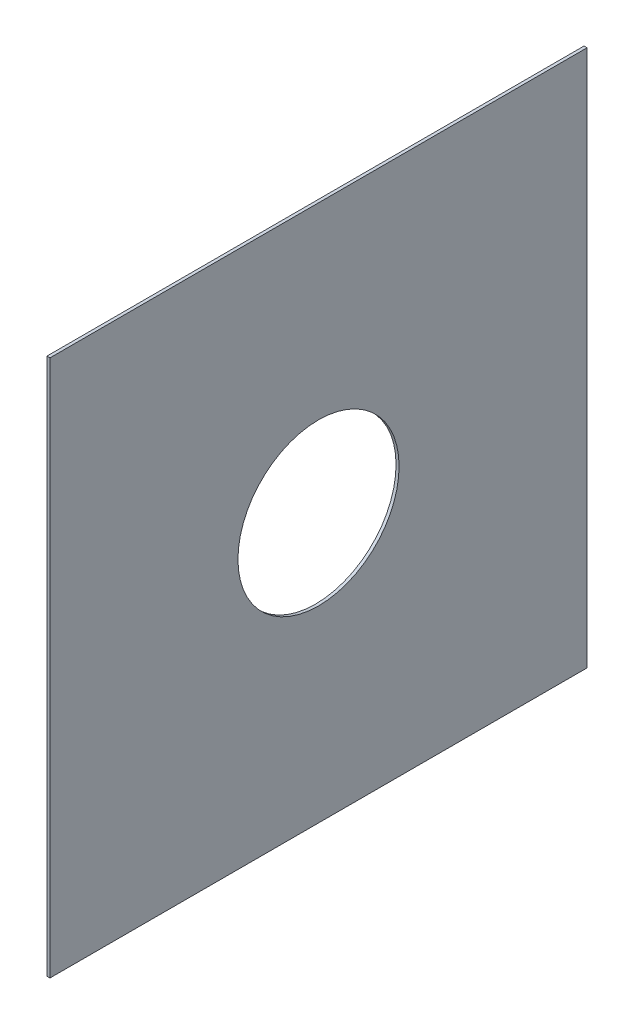
SolidWorks part; units mm, degrees
ref_plane "Alzado" through (0, 0, 0) normal (0, 0, 1) x (1, 0, 0)
ref_plane "Planta" through (0, 0, 0) normal (0, 1, 0) x (1, 0, 0)
ref_plane "Vista lateral" through (0, 0, 0) normal (1, 0, 0) x (0, 0, -1)
sketch "Croquis1" plane through (0, 0, 0) normal (1, 0, 0) x (0, -1, 0)
  line L1 (265, -265) -> (-265, -265)
  line L2 (265, -265) -> (265, 265)
  line L3 (265, 265) -> (-265, 265)
  line L4 (-265, -265) -> (-265, 265)
  line L5 (265, -265) -> (-265, 265) construction
  line L6 (265, 265) -> (-265, -265) construction
  point P0 (0, 0)
  dimension "D1" = 530
  dimension "D2" = 530
extrude "Extruir1" add sketch "Croquis1" along normal blind 3
sketch "Croquis3" plane through (0, 0, 0) normal (-1, 0, 0) x (0, 0, 1)
  line L0 (0, 265) -> (0, -265) construction
  line L1 (-265, 265) -> (265, 265) construction
  line L2 (265, -265) -> (-265, -265) construction
  circle A0 centre (0, 0) radius 79.5
  dimension "D1" = 159
extrude "Extruir2" cut sketch "Croquis3" against normal through all
